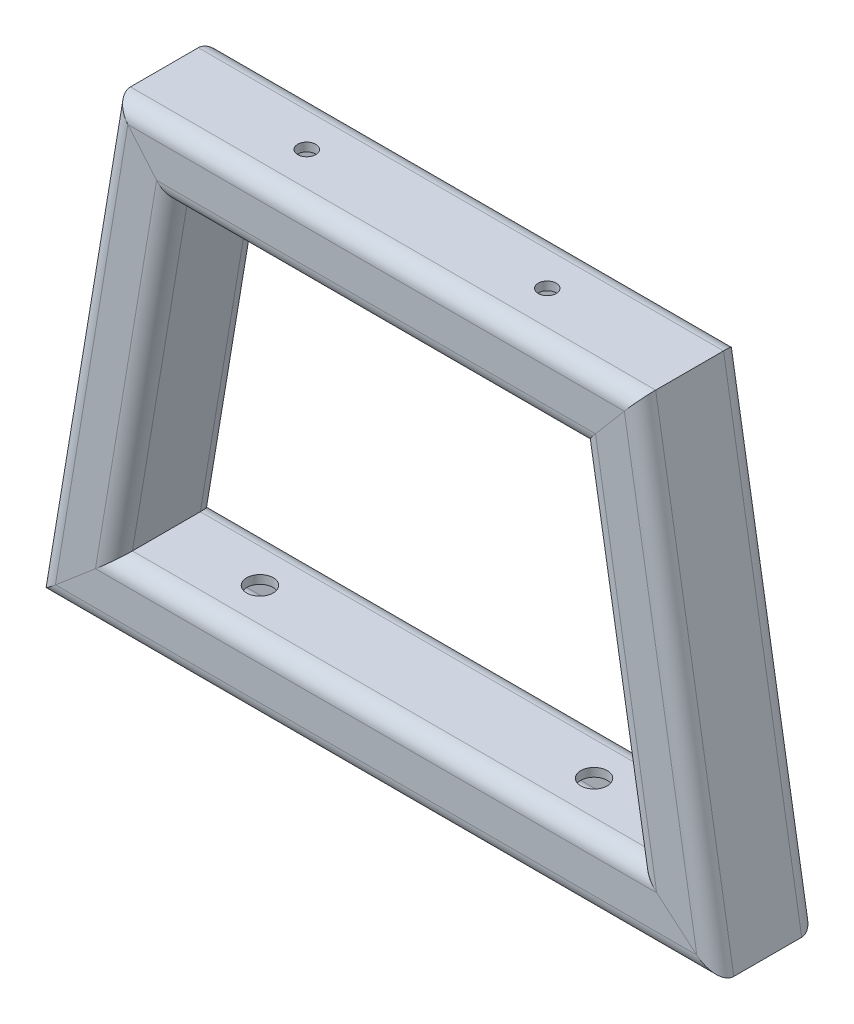
SolidWorks part; units mm, degrees
material "Plain Carbon Steel"
ref_plane "Front Plane" through (0, 0, 0) normal (0, 0, 1) x (1, 0, 0)
ref_plane "Top Plane" through (0, 0, 0) normal (0, 1, 0) x (1, 0, 0)
ref_plane "Right Plane" through (0, 0, 0) normal (1, 0, 0) x (0, 0, -1)
sketch "Sketch1" plane through (0, 0, 0) normal (0, 0, 1) x (1, 0, 0)
  line L0 (-175, 0) -> (175, 0)
  line L1 (175, 0) -> (225, -300)
  line L2 (225, -300) -> (-225, -300)
  line L3 (-225, -300) -> (-175, 0)
  line L4 (0, -41.91) -> (0, 41.91) construction
  point P3 (0, 0)
  point P6 (0, -300)
  dimension "D1" = 350
  dimension "D2" = 300
  dimension "D3" = 450
other "Structural Member1"
ref_plane "Plane1"
sketch "Sketch141" plane through (-175, 0, 0) normal (1, 0, 0) x (0, 1, 0)
  line L0 (-12.7, -31.75) -> (12.7, -31.75)
  line L1 (-19.05, -25.4) -> (-19.05, 25.4)
  line L2 (12.7, 31.75) -> (-12.7, 31.75)
  line L3 (19.05, 25.4) -> (19.05, -25.4)
  line L4 (-12.7, -38.1) -> (12.7, -38.1)
  line L5 (-25.4, -25.4) -> (-25.4, 25.4)
  line L6 (12.7, 38.1) -> (-12.7, 38.1)
  line L7 (25.4, 25.4) -> (25.4, -25.4)
  line L8 (0, 0) -> (25.4, 0) construction
  line L9 (0, 0) -> (0, 38.1) construction
  arc A0 (25.4, 25.4) -> (12.7, 38.1) centre (12.7, 25.4) ccw
  arc A1 (12.7, -38.1) -> (25.4, -25.4) centre (12.7, -25.4) ccw
  arc A2 (-25.4, -25.4) -> (-12.7, -38.1) centre (-12.7, -25.4) ccw
  arc A3 (-12.7, 38.1) -> (-25.4, 25.4) centre (-12.7, 25.4) ccw
  arc A4 (-12.7, 31.75) -> (-19.05, 25.4) centre (-12.7, 25.4) ccw
  arc A5 (19.05, 25.4) -> (12.7, 31.75) centre (12.7, 25.4) ccw
  arc A6 (12.7, -31.75) -> (19.05, -25.4) centre (12.7, -25.4) ccw
  arc A7 (-19.05, -25.4) -> (-12.7, -31.75) centre (-12.7, -25.4) ccw
  point P3 (0, -38.1)
  point P4 (-25.4, 0)
  point P5 (0, 0)
  point P6 (25.4, -38.1)
  point P7 (-25.4, -38.1)
  point P8 (-25.4, 38.1)
  point P33 (0, 0)
  point P35 (25.4, 38.1)
  point P36 (25.4, 0)
  point P37 (0, 38.1)
  dimension "D1" = 12.7
  dimension "Thickness" = 6.35
  dimension "V_leg" = 76.2
  dimension "H_leg" = 50.8
hole_wizard "1/2 Clearance Hole1" positions "3DSketch1" profile "Sketch143" hole size "1/2" standard "Ansi Inch"
sketch3d "3DSketch1"
  point P0 (90, 25.4, 0)
  dimension "D1" = 90
sketch "Sketch143" plane through (90, 25.4, 0) normal (1, 0, 0) x (0, 0, 1)
  line L0 (0, 0) -> (0, 54.8535)
  line L1 (0, 54.8535) -> (6.7462, 50.8)
  line L2 (6.7462, 50.8) -> (6.7462, 0)
  line L5 (6.7462, 0) -> (0, 0)
  line L10 (0, 54.8535) -> (-6.7462, 50.8) construction
  line L11 (0, -6.35) -> (0, 107.95) construction
  dimension "Hole Dia." = 13.4925
  dimension "Hole Depth" = 50.8
  dimension "Drill Angle" = 118
mirror "Mirror1" about plane through (0, 0, 0) normal (1, 0, 0) of "1/2 Clearance Hole1"
hole_wizard "3/4 Clearance Hole2" positions "3DSketch2" profile "Sketch144" hole size "3/4" standard "Ansi Inch"
sketch3d "3DSketch2"
  point P0 (125, -274.6, 0)
  dimension "D1" = 125
sketch "Sketch144" plane through (125, -274.6, 0) normal (1, 0, 0) x (0, 0, 1)
  line L0 (0, 0) -> (0, 56.7613)
  line L1 (0, 56.7613) -> (9.9212, 50.8)
  line L2 (9.9212, 50.8) -> (9.9212, 0)
  line L5 (9.9212, 0) -> (0, 0)
  line L10 (0, 56.7613) -> (-9.9212, 50.8) construction
  line L11 (0, -6.35) -> (0, 107.95) construction
  dimension "Hole Dia." = 19.8425
  dimension "Hole Depth" = 50.8
  dimension "Drill Angle" = 118
mirror "Mirror2" about plane through (0, 0, 0) normal (1, 0, 0) of "3/4 Clearance Hole2"
